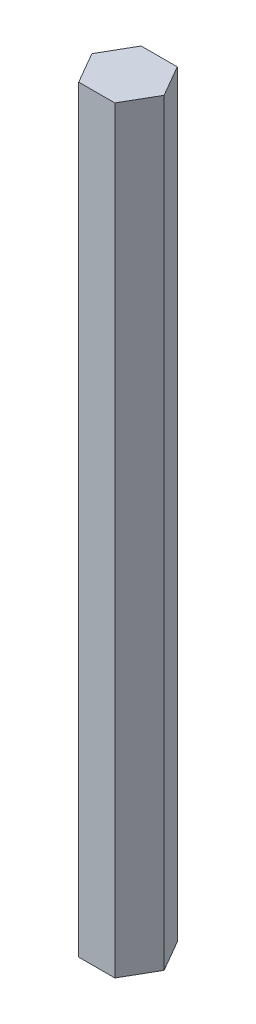
SolidWorks part; units mm, degrees
ref_plane "Front Plane" through (0, 0, 0) normal (0, 0, 1) x (1, 0, 0)
ref_plane "Top Plane" through (0, 0, 0) normal (0, 1, 0) x (1, 0, 0)
ref_plane "Right Plane" through (0, 0, 0) normal (1, 0, 0) x (0, 0, -1)
sketch "Sketch1" plane through (0, 0, 0) normal (0, 1, 0) x (1, 0, 0)
  line L1 (3, 0) -> (1.5, 2.5981)
  line L2 (1.5, 2.5981) -> (-1.5, 2.5981)
  line L3 (-1.5, 2.5981) -> (-3, 0)
  line L4 (-3, 0) -> (-1.5, -2.5981)
  line L5 (-1.5, -2.5981) -> (1.5, -2.5981)
  line L6 (1.5, -2.5981) -> (3, 0)
  circle A0 centre (0, 0) radius 2.5981 construction
  dimension "D1" = 3
extrude "Boss-Extrude1" add sketch "Sketch1" along normal blind 63
sketch "Sketch3" plane through (0, 0, 0) normal (0, -1, 0) x (1, 0, 0)
  circle A0 centre (0, 0) radius 1.6
  dimension "D1" = 3.2
extrude "Cut-Extrude1" cut sketch "Sketch3" against normal blind 5
